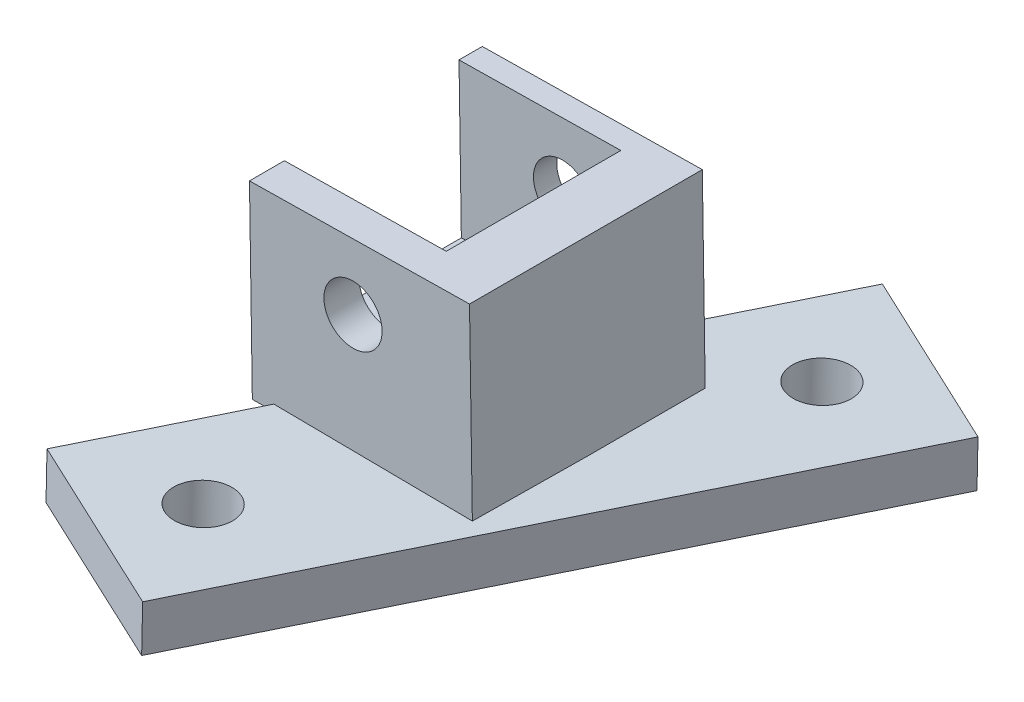
SolidWorks part; units mm, degrees
ref_plane "Front Plane" through (0, 0, 0) normal (0, 0, 1) x (1, 0, 0)
ref_plane "Top Plane" through (0, 0, 0) normal (0, 1, 0) x (1, 0, 0)
ref_plane "Right Plane" through (0, 0, 0) normal (1, 0, 0) x (0, 0, -1)
sketch "Sketch1" plane through (0, 0, 0) normal (0, 0, 1) x (1, 0, 0)
  line L0 (616.5962, 110.6556) -> (616.9091, 90.1601)
  line L1 (604.7125, 110.4741) -> (634.2525, 110.9251) construction
  line L2 (616.9091, 90.1601) -> (640.9147, 90.5267)
  line L3 (640.9147, 90.5267) -> (640.6018, 111.0221)
  line L4 (640.6018, 111.0221) -> (616.5962, 110.6556)
  line L5 (606.4491, 93.8109) -> (629.5989, 94.1643) construction
  line L6 (606.4491, 93.8109) -> (629.5989, 94.1643)
  arc A0 (634.4712, 96.6012) -> (634.2525, 110.9251) centre (627.8931, 103.6644) ccw construction
  arc A1 (629.5989, 94.1643) -> (634.4712, 96.6012) centre (627.8931, 103.6644) ccw construction
  arc A2 (634.4712, 96.6012) -> (634.2525, 110.9251) centre (627.8931, 103.6644) ccw
  arc A3 (629.5989, 94.1643) -> (634.4712, 96.6012) centre (627.8931, 103.6644) ccw
  dimension "D1" = 3.81
  dimension "D2" = 6.35
  dimension "D3" = 24.0084
extrude "Boss-Extrude1" add sketch "Sketch1" against normal blind 21.59 contours A3 L6 L0 L2 L3 L4 A2
sketch "Sketch2" plane through (0, 0, -19.05) normal (0, 0, -1) x (-1, 0, 0)
  line L0 (-616.8509, 93.9697) -> (-616.5962, 110.6556)
  line L1 (-604.6203, 110.4727) -> (-634.2525, 110.9251) construction
  line L2 (-616.5962, 110.6556) -> (-634.2525, 110.9251)
  line L3 (-616.8509, 93.9697) -> (-629.5989, 94.1643) construction
  line L4 (-616.8509, 93.9697) -> (-629.5989, 94.1643)
  arc A0 (-634.2525, 110.9251) -> (-629.5989, 94.1643) centre (-627.8931, 103.6644) ccw construction
  arc A1 (-634.2525, 110.9251) -> (-629.5989, 94.1643) centre (-627.8931, 103.6644) ccw
  circle A2 centre (-627.8931, 103.6644) radius 3.175
  dimension "D1" = 6.35
extrude "Boss-Extrude2" add sketch "Sketch2" along normal up to surface (2.54 mm away) up to face at (630.7326, 98.2176, -21.59)
sketch "Sketch3" plane through (0, 0, 0) normal (0, 0, 1) x (1, 0, 0)
  line L0 (616.5962, 110.6556) -> (640.6018, 111.0221)
  line L1 (640.6018, 111.0221) -> (640.9147, 90.5267)
  line L2 (640.9147, 90.5267) -> (616.9091, 90.1601)
  line L3 (616.9091, 90.1601) -> (640.9147, 90.5267)
  line L4 (616.5962, 110.6556) -> (616.9091, 90.1601)
  circle A0 centre (627.8931, 103.6644) radius 3.175
  arc M1 (634.2525, 110.9251) -> (629.5989, 94.1643) centre (627.8931, 103.6644) cw
  line M2 (629.5989, 94.1643) -> (616.8509, 93.9697)
  line M3 (616.8509, 93.9697) -> (616.9091, 90.1601)
  line M4 (616.9091, 90.1601) -> (640.9147, 90.5267)
  line M5 (640.9147, 90.5267) -> (640.6018, 111.0221)
  line M6 (640.6018, 111.0221) -> (634.2525, 110.9251)
  dimension "D1" = 6.35
extrude "Boss-Extrude3" add sketch "Sketch3" along normal blind 3.81 contours L0 L4 A0 M2 M1 | M6 M1 M2 M3 M4 M5
ref_plane "Plane1" through (1.0096, 97.2566, -1.0889) normal (0.0104, 0.9999, -0.0112) x (0.9999, -0.0104, 0.0001)
sketch "Sketch6" plane through (1.0096, 97.2566, -1.0889) normal (0.0104, 0.9999, -0.0112) x (0.9999, -0.0104, 0.0001)
  line L9 (629.9704, -30.8308) -> (658.9642, 31.3189)
  line L10 (658.9642, 31.3189) -> (639.3986, 40.4465)
  line L11 (639.3986, 40.4465) -> (610.4048, -21.7031)
  line L12 (610.4048, -21.7031) -> (629.9704, -30.8308)
  line L13 (615.9376, 20.5793) -> (639.9381, 20.5752) construction
  circle A2 centre (623.9461, -18.2105) radius 3.175
  circle A3 centre (645.423, 27.8263) radius 3.175
  dimension "D5" = 17.78
  dimension "D9" = 8.89
  dimension "D10" = 10.795
  dimension "D2" = 12.7
  dimension "D1" = 65
  dimension "D6" = 6.35
  dimension "D7" = 6.35
  dimension "D3" = 21.59
  dimension "D4" = 68.58
  dimension "D8" = 8.89
  dimension "D11" = 10.795
extrude "Boss-Extrude4" add sketch "Sketch6" against normal blind 5.08
